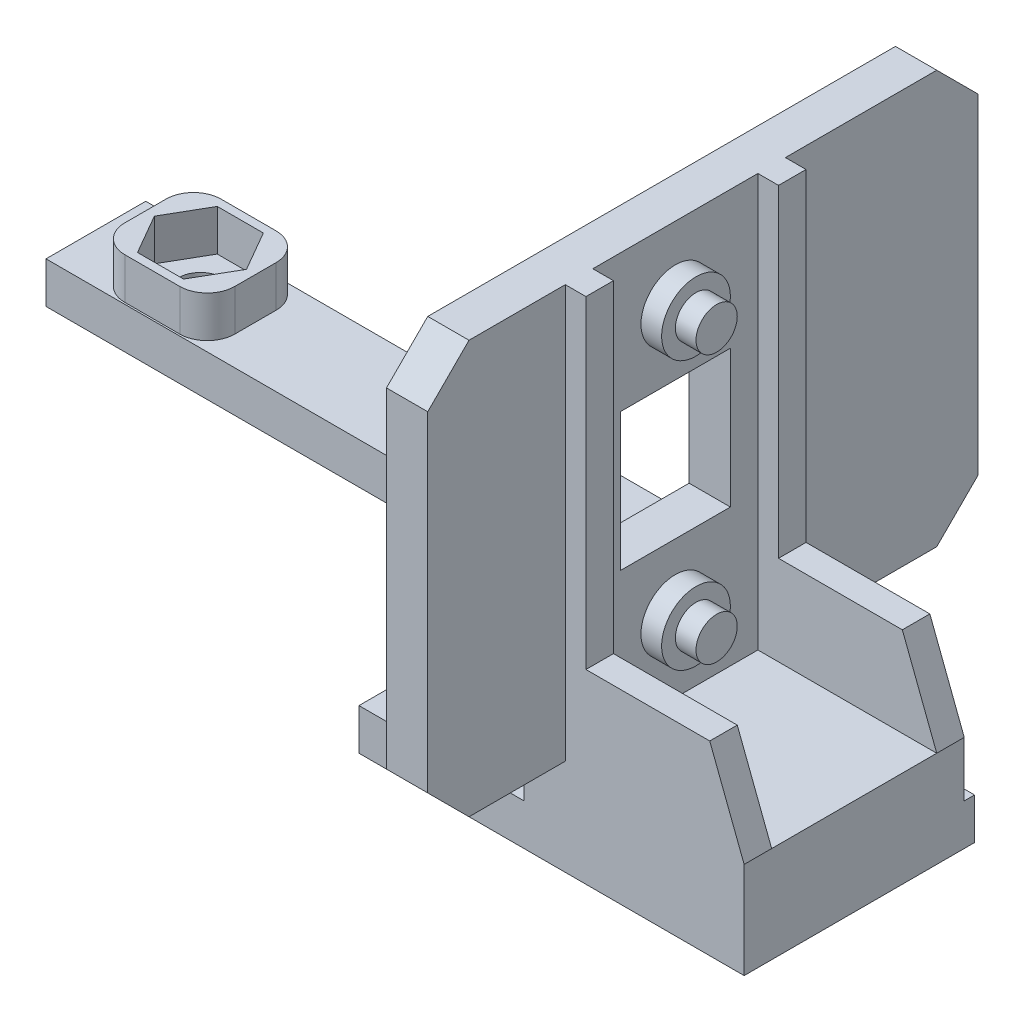
SolidWorks part; units mm, degrees
ref_plane "Front Plane" through (0, 0, 0) normal (0, 0, 1) x (1, 0, 0)
ref_plane "Top Plane" through (0, 0, 0) normal (0, 1, 0) x (1, 0, 0)
ref_plane "Right Plane" through (0, 0, 0) normal (1, 0, 0) x (0, 0, -1)
sketch "Sketch1" plane through (0, 0, 0) normal (0, 1, 0) x (1, 0, 0)
  line L0 (0, 0) -> (0, -16.75)
  line L1 (0, 0) -> (-56, 0)
  line L2 (0, 0) -> (0, 7.25)
  line L3 (0, 7.25) -> (-56, 7.25)
  line L4 (-56, 0) -> (-56, 7.25)
  line L5 (0, -16.75) -> (-16.5, -16.75)
  line L6 (-16.5, -16.75) -> (-16.5, 0)
  line L7 (0, 0) -> (11.5, 0)
  line L8 (11.5, 0) -> (11.5, -16.75)
  line L9 (11.5, -16.75) -> (0, -16.75)
  line L10 (-5, 0) -> (-5, -16.75)
  circle A0 centre (-48.4, 3.625) radius 1.6
  circle A1 centre (-7.6, 3.625) radius 1.6
  point P13 (-56, 3.625)
  dimension "D4" = 3.2
  dimension "D5" = 3.2
  dimension "D1" = 7.25
  dimension "D2" = 56
  dimension "D3" = 16.75
  dimension "D6" = 7.6
  dimension "D7" = 7.6
  dimension "D8" = 16.5
  dimension "D9" = 16.5
  dimension "D10" = 11.5
extrude "Boss-Extrude1" add sketch "Sketch1" along normal blind 3 contours L4 L1 L2 L3 A1 A0 | L1 L10 L5 L0 | L9 L8 L7 L0 | L10 L1 L6 L5
sketch "Sketch2" plane through (0, 3, 0) normal (0, 1, 0) x (1, 0, 0)
  line L1 (-52.4, 7.125) -> (-44.4, 7.125)
  line L2 (-52.4, 7.125) -> (-52.4, 0.125)
  line L3 (-52.4, 0.125) -> (-44.4, 0.125)
  line L4 (-44.4, 7.125) -> (-44.4, 0.125)
  line L5 (-52.4, 7.125) -> (-44.4, 0.125) construction
  line L6 (-52.4, 0.125) -> (-44.4, 7.125) construction
  line L7 (-46.7257, 0.725) -> (-45.0514, 3.625)
  line L8 (-45.0514, 3.625) -> (-46.7257, 6.525)
  line L9 (-46.7257, 6.525) -> (-50.0743, 6.525)
  line L10 (-50.0743, 6.525) -> (-51.7486, 3.625)
  line L11 (-51.7486, 3.625) -> (-50.0743, 0.725)
  line L12 (-50.0743, 0.725) -> (-46.7257, 0.725)
  line L13 (-11.6, 7.125) -> (-3.6, 7.125)
  line L14 (-11.6, 7.125) -> (-11.6, 0.125)
  line L15 (-11.6, 0.125) -> (-3.6, 0.125)
  line L16 (-3.6, 7.125) -> (-3.6, 0.125)
  line L17 (-11.6, 7.125) -> (-3.6, 0.125) construction
  line L18 (-11.6, 0.125) -> (-3.6, 7.125) construction
  line L19 (-5.9257, 0.725) -> (-4.2514, 3.625)
  line L20 (-4.2514, 3.625) -> (-5.9257, 6.525)
  line L21 (-5.9257, 6.525) -> (-9.2743, 6.525)
  line L22 (-9.2743, 6.525) -> (-10.9486, 3.625)
  line L23 (-10.9486, 3.625) -> (-9.2743, 0.725)
  line L24 (-9.2743, 0.725) -> (-5.9257, 0.725)
  circle A0 centre (-48.4, 3.625) radius 2.9 construction
  circle A1 centre (-7.6, 3.625) radius 2.9 construction
  point P0 (-48.4, 3.625)
  point P7 (-7.6, 3.625)
  dimension "D1" = 8
  dimension "D2" = 7
  dimension "D3" = 5.8
  dimension "D4" = 7
  dimension "D5" = 8
  dimension "D6" = 5.8
extrude "Boss-Extrude2" add sketch "Sketch2" along normal blind 3
fillet "Fillet1" radius 2 8 edges at (-11.6, 4.5, -7.125) (-11.6, 4.5, -0.125) (-3.6, 4.5, -0.125) (-3.6, 4.5, -7.125) (-44.4, 4.5, -0.125) (-44.4, 4.5, -7.125) (-52.4, 4.5, -7.125) (-52.4, 4.5, -0.125)
sketch "Sketch3" plane through (0, 3, 0) normal (0, 1, 0) x (1, 0, 0)
  line L0 (11.5, -0.75) -> (-4.5, -0.75)
  line L1 (11.5, 0) -> (11.5, -16.75) construction
  line L2 (-4.5, -0.75) -> (-4.5, -16.75)
  line L3 (11.5, -16.75) -> (-16.5, -16.75) construction
  line L4 (-4.5, -16.75) -> (11.5, -16.75)
  line L5 (11.5, -16.75) -> (11.5, -0.75)
  dimension "D1" = 16
  dimension "D2" = 16
extrude "Boss-Extrude3" add sketch "Sketch3" along normal blind 4
sketch "Sketch5" plane through (-4.5, 0, 0) normal (-1, 0, 0) x (0, 0, 1)
  line L0 (0.75, 7) -> (16.75, 7) construction
  line L1 (0.75, 7) -> (16.75, 7)
  line L2 (16.75, 7) -> (26.75, 7)
  line L3 (26.75, 7) -> (26.75, 37)
  line L4 (26.75, 37) -> (-13.25, 37)
  line L5 (-13.25, 37) -> (-13.25, 7)
  line L6 (-13.25, 7) -> (0.75, 7)
  line L7 (0.75, 7) -> (0.75, 3) construction
  line L8 (16.75, 7) -> (16.75, 3) construction
  dimension "D1" = 14
  dimension "D2" = 30
  dimension "D3" = 10
extrude "Boss-Extrude4" add sketch "Sketch5" against normal blind 3
sketch "Sketch6" plane through (0, 0, 16.75) normal (0, 0, 1) x (1, 0, 0)
  line L0 (-1.5, 37) -> (0, 37)
  line L1 (0, 37) -> (11.5, 7)
  line L2 (11.5, 7) -> (-1.5, 7)
  line L3 (-1.5, 7) -> (-1.5, 37)
extrude "Boss-Extrude5" add sketch "Sketch6" against normal blind 2
sketch "Sketch7" plane through (0, 0, 0.75) normal (0, 0, -1) x (-1, 0, 0)
  line L4 (1.5, 37) -> (0, 37)
  line L5 (0, 37) -> (-11.5, 7)
  line L6 (-11.5, 7) -> (1.5, 7)
  line L7 (1.5, 7) -> (1.5, 37)
  line L8 (1.5, 37) -> (0, 37)
  line L9 (0, 37) -> (-11.5, 7)
  line L10 (-11.5, 7) -> (1.5, 7)
  line L11 (1.5, 7) -> (1.5, 37)
  dimension "D1" = 0
extrude "Boss-Extrude6" add sketch "Sketch7" against normal blind 2
chamfer "Chamfer1" distance 3 angle 45 4 edges at (-3, 7, -13.25) (-3, 7, 26.75) (-3, 37, 26.75) (-3, 37, -13.25)
sketch "Sketch8" plane through (-1.5, 0, 0) normal (1, 0, 0) x (0, 0, -1)
  line L6 (-14.75, 37) -> (-14.75, 7) construction
  line L7 (-12.75, 27) -> (-4.75, 27)
  line L8 (-12.75, 27) -> (-12.75, 17)
  line L9 (-12.75, 17) -> (-4.75, 17)
  line L10 (-4.75, 27) -> (-4.75, 17)
  line L12 (-14.75, 37) -> (-2.75, 37) construction
  dimension "D1" = 8
  dimension "D2" = 10
  dimension "D3" = 2
  dimension "D4" = 10
extrude "Cut-Extrude1" cut sketch "Sketch8" against normal blind 10
sketch "Sketch9" plane through (0, 0, 16.75) normal (0, 0, 1) x (1, 0, 0)
  line L0 (0, 37) -> (0, 13.5217)
  line L1 (0, 13.5217) -> (9, 13.5217)
  line L2 (11.5, 7) -> (0, 37) construction
  dimension "D1" = 9
extrude "Cut-Extrude2" cut sketch "Sketch9" against normal blind 2 and the other way through all
sketch "Sketch10" plane through (0, 0, 2.75) normal (0, 0, 1) x (1, 0, 0)
  line L0 (0, 37) -> (0, 13.5217)
  line L1 (0, 13.5217) -> (9, 13.5217)
  dimension "D1" = 9
extrude "Cut-Extrude3" cut sketch "Sketch10" against normal blind 2 and the other way through all
sketch "Sketch11" plane through (-1.5, 0, 0) normal (1, 0, 0) x (0, 0, -1)
  line L0 (-8.75, 37) -> (-8.75, 7) construction
  line L1 (-14.75, 37) -> (-2.75, 37) construction
  line L2 (-14.75, 7) -> (-2.75, 7) construction
  line L3 (-12.75, 22) -> (-4.75, 22) construction
  line L4 (-12.75, 27) -> (-12.75, 17) construction
  line L5 (-4.75, 17) -> (-4.75, 27) construction
  circle A0 centre (-8.75, 31.75) radius 1.5
  circle A1 centre (-8.75, 12.25) radius 1.5
  dimension "D1" = 9.75
extrude "Boss-Extrude7" add sketch "Sketch11" along normal blind 3
sketch "Sketch13" plane through (-1.5, 0, 0) normal (1, 0, 0) x (0, 0, -1)
  circle A0 centre (-8.75, 31.75) radius 2.5
  circle A1 centre (-8.75, 12.25) radius 2.5
extrude "Boss-Extrude8" add sketch "Sketch13" along normal blind 1.5
